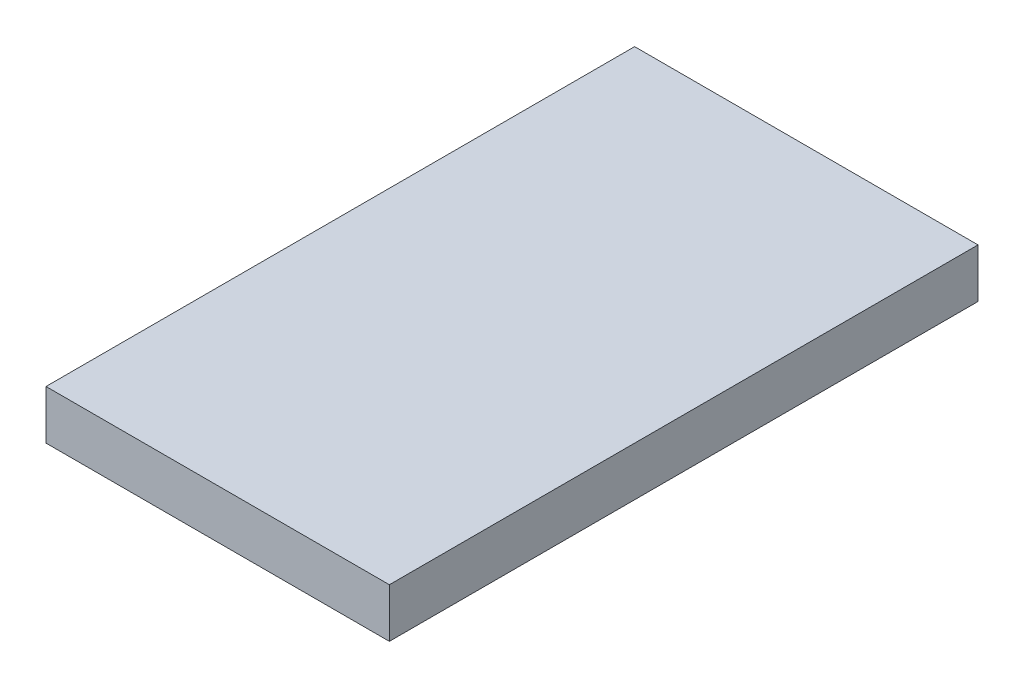
SolidWorks part; units mm, degrees
ref_plane "Front Plane" through (0, 0, 0) normal (0, 0, 1) x (1, 0, 0)
ref_plane "Top Plane" through (0, 0, 0) normal (0, 1, 0) x (1, 0, 0)
ref_plane "Right Plane" through (0, 0, 0) normal (1, 0, 0) x (0, 0, -1)
sketch "Sketch1" plane through (0, 0, 0) normal (0, 1, 0) x (1, 0, 0)
  line L1 (-21, 36) -> (21, 36)
  line L2 (-21, 36) -> (-21, -36)
  line L3 (-21, -36) -> (21, -36)
  line L4 (21, 36) -> (21, -36)
  line L5 (-21, 36) -> (21, -36) construction
  line L6 (-21, -36) -> (21, 36) construction
  point P0 (0, 0)
  dimension "D1" = 42
  dimension "D2" = 72
extrude "Boss-Extrude1" add sketch "Sketch1" along normal blind 6
sketch "Sketch2" plane through (0, 6, 0) normal (0, 1, 0) x (1, 0, 0)
  line L0 (0, 0) -> (0, -42.4327) construction
  line L1 (0, 0) -> (-28.4874, 0) construction
  line L2 (-21, 36) -> (-21, -36) construction
  line L3 (-21, -36) -> (21, -36) construction
  circle A0 centre (-12, -33) radius 1.5
  circle A1 centre (-18, -20) radius 1.5
  circle A2 centre (18, -20) radius 1.5
  circle A3 centre (12, -33) radius 1.5
  circle A4 centre (12, 33) radius 1.5
  circle A5 centre (18, 20) radius 1.5
  circle A6 centre (-18, 20) radius 1.5
  circle A7 centre (-12, 33) radius 1.5
  dimension "D1" = 3
  dimension "D4" = 3
  dimension "D6" = 3
  dimension "D2" = 20
  dimension "D3" = 3
  dimension "D5" = 12
